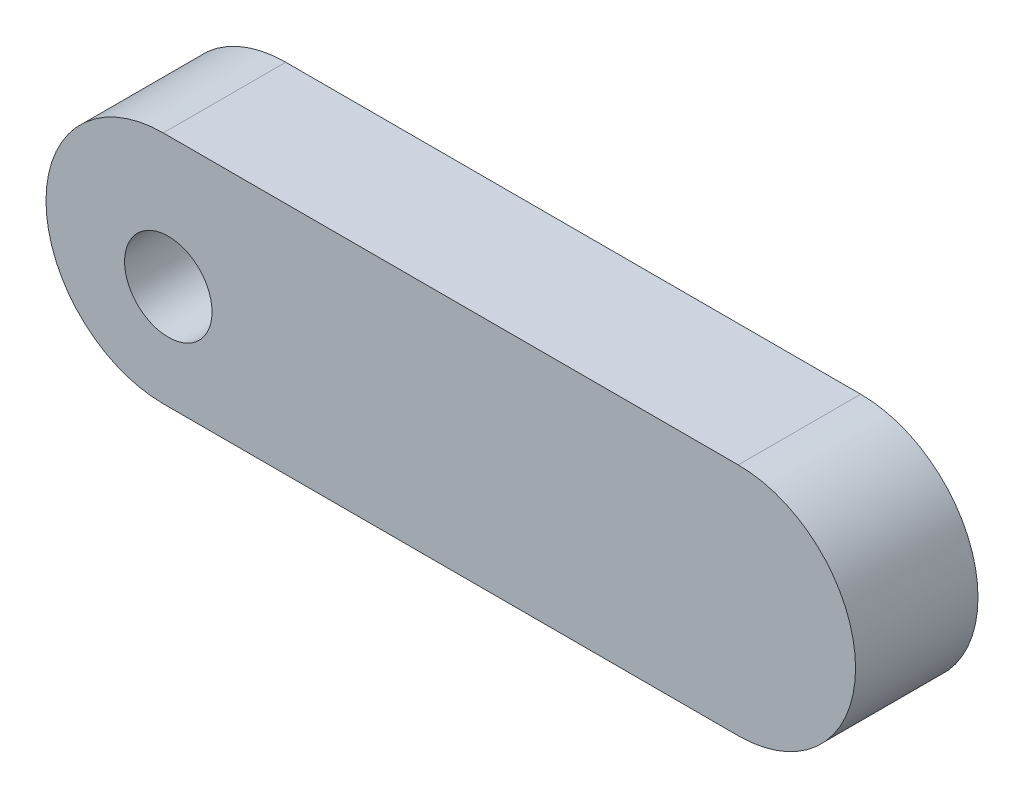
SolidWorks part; units mm, degrees
ref_plane "前视基准面" through (0, 0, 0) normal (0, 0, 1) x (1, 0, 0)
ref_plane "上视基准面" through (0, 0, 0) normal (0, 1, 0) x (1, 0, 0)
ref_plane "右视基准面" through (0, 0, 0) normal (1, 0, 0) x (0, 0, -1)
sketch "草图1" plane through (0, 0, 0) normal (0, 0, 1) x (1, 0, 0)
  line L0 (-68.6434, 21.7989) -> (-21.6917, 21.7989) construction
  line L1 (-68.6434, 31.3771) -> (-21.6917, 31.3771)
  line L2 (-68.6434, 12.2207) -> (-21.6917, 12.2207)
  arc A0 (-68.6434, 31.3771) -> (-68.6434, 12.2207) centre (-68.6434, 21.7989) ccw
  arc A1 (-21.6917, 12.2207) -> (-21.6917, 31.3771) centre (-21.6917, 21.7989) ccw
  point P2 (-45.1676, 21.7989)
extrude "凸台-拉伸1" add sketch "草图1" along normal blind 10
sketch "草图2" plane through (0, 0, 10) normal (0, 0, 1) x (1, 0, 0)
  circle A0 centre (-68.2341, 20.7072) radius 3.5706
  circle A1 centre (-42.8081, 24.2778) radius 4.0128
extrude "切除-拉伸1" cut sketch "草图2" against normal blind 10 contours A0
